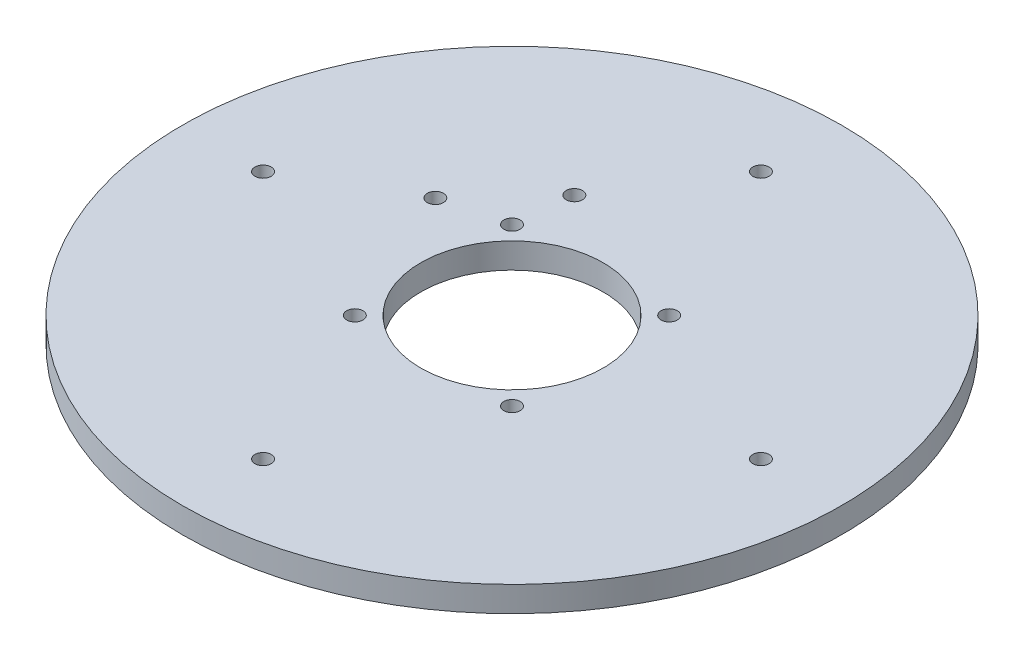
SolidWorks part; units mm, degrees
ref_plane "前视基准面" through (0, 0, 0) normal (0, 0, 1) x (1, 0, 0)
ref_plane "上视基准面" through (0, 0, 0) normal (0, 1, 0) x (1, 0, 0)
ref_plane "右视基准面" through (0, 0, 0) normal (1, 0, 0) x (0, 0, -1)
other "Configuration Table"
sketch "草图2" plane through (0, 0, 0) normal (0, 1, 0) x (1, 0, 0)
  line L1 (-23, -23) -> (23, -23)
  line L2 (-23, -23) -> (-23, 23)
  line L3 (-23, 23) -> (23, 23)
  line L4 (23, -23) -> (23, 23)
  line L5 (-23, -23) -> (23, 23) construction
  line L6 (-23, 23) -> (23, -23) construction
  circle A0 centre (0, 0) radius 18
extrude "凸台-拉伸1" add sketch "草图2" along normal blind 5
fillet "圆角1" radius 5.5 4 edges at (23, 2.5, 23) (23, 2.5, -23) (-23, 2.5, -23) (-23, 2.5, 23)
sketch "草图3" plane through (0, 5, 0) normal (0, 1, 0) x (1, 0, 0)
  line L1 (-15.5, -15.5) -> (15.5, -15.5)
  line L2 (-15.5, -15.5) -> (-15.5, 15.5)
  line L3 (-15.5, 15.5) -> (15.5, 15.5)
  line L4 (15.5, -15.5) -> (15.5, 15.5)
  line L5 (-15.5, -15.5) -> (15.5, 15.5) construction
  line L6 (-15.5, 15.5) -> (15.5, -15.5) construction
  circle A0 centre (-15.5, 15.5) radius 1.6
  circle A1 centre (15.5, 15.5) radius 1.6
  circle A2 centre (-15.5, -15.5) radius 1.6
  circle A3 centre (15.5, -15.5) radius 1.6
  point P0 (0, 0)
extrude "切除-拉伸1" cut sketch "草图3" against normal through all contours A2 | A0 | A1 | A3
sketch "草图4" plane through (0, 5, 0) normal (0, 1, 0) x (1, 0, 0)
  circle A1 centre (-49.1, 0) radius 1.6
  circle A2 centre (0, -49.1) radius 1.6
  circle A3 centre (49.1, 0) radius 1.6
  circle A4 centre (0, 49.1) radius 1.6
  circle A5 centre (0, 0) radius 65
  circle M3 centre (15.5, -15.5) radius 1.6
  circle M4 centre (15.5, 15.5) radius 1.6
  circle M5 centre (-15.5, 15.5) radius 1.6
  circle M6 centre (-15.5, -15.5) radius 1.6
  line M7 (-17.5, -23) -> (17.5, -23)
  arc M8 (17.5, -23) -> (23, -17.5) centre (17.5, -17.5) ccw
  line M9 (23, -17.5) -> (23, 17.5)
  arc M10 (23, 17.5) -> (17.5, 23) centre (17.5, 17.5) ccw
  line M11 (17.5, 23) -> (-17.5, 23)
  arc M12 (-17.5, 23) -> (-23, 17.5) centre (-17.5, 17.5) ccw
  line M13 (-23, 17.5) -> (-23, -17.5)
  arc M14 (-23, -17.5) -> (-17.5, -23) centre (-17.5, -17.5) ccw
  circle M15 centre (0, 0) radius 18
extrude "凸台-拉伸2" add sketch "草图4" against normal blind 5 contours M14 M7 M8 M9 M10 M11 M12 M13 M4 M6 M15 M5 M3 | A5 A1 A2 A3 A4 M7 M14 M13 M12 M11 M10 M9 M8
sketch "草图7" plane through (0, 5, 0) normal (0, 1, 0) x (1, 0, 0)
  circle A2 centre (-14.3834, 26.6827) radius 1.6
  circle A3 centre (-27.6166, 12.4968) radius 1.6
extrude "切除-拉伸3" cut sketch "草图7" against normal through all
